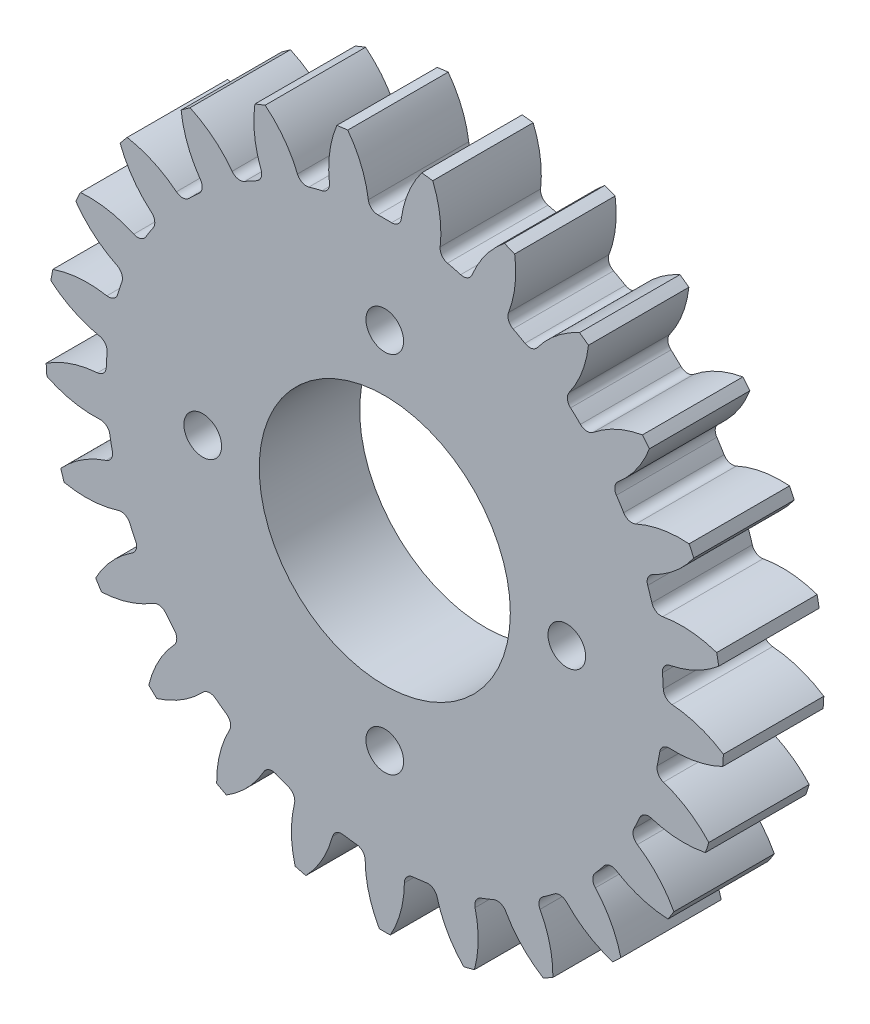
SolidWorks part; units mm, degrees
ref_plane "Front Plane" through (0, 0, 0) normal (0, 0, 1) x (1, 0, 0)
ref_plane "Top Plane" through (0, 0, 0) normal (0, 1, 0) x (1, 0, 0)
ref_plane "Right Plane" through (0, 0, 0) normal (1, 0, 0) x (0, 0, -1)
sketch "Sketch1" plane through (0, 0, 0) normal (0, 0, 1) x (1, 0, 0)
  line L0 (0, 0) -> (-18.1989, 0) construction
  line L1 (0, 0) -> (0, 8.2854) construction
  circle A0 centre (0, 0) radius 5
  circle A1 centre (0, 0) radius 13.5
  circle A2 centre (-7.25, 0) radius 0.75
  circle A3 centre (0, 7.25) radius 0.75
  circle A4 centre (7.25, 0) radius 0.75
  circle A5 centre (0, -7.25) radius 0.75
  point P19 (0, 0)
  dimension "D1" = 10
  dimension "D2" = 27
  dimension "D3" = 1.5
  dimension "D4" = 7.25
  dimension "D5" = 4
extrude "Boss-Extrude1" add sketch "Sketch1" along normal blind 10
sketch "Sketch2" plane through (0, 0, 10) normal (0, 0, 1) x (1, 0, 0)
  line L0 (0, 0) -> (0, 13.5) construction
  line L1 (-0.6232, 11.0825) -> (0, 0) construction
  line L2 (0, 9.9064) -> (-3.5205, 19.5789) construction
  circle A0 centre (0, 0) radius 13.5 construction
  arc A1 (0.6232, 11.0825) -> (-0.6232, 11.0825) centre (0, 0) ccw
  arc A2 (0.9345, 12.465) -> (-0.9345, 12.465) centre (0, 0) ccw construction
  arc A3 (-1.4738, 13.4193) -> (-0.6232, 11.0825) centre (-4.9231, 10.8407) cw
  arc A4 (1.4738, 13.4193) -> (0.6232, 11.0825) centre (4.9231, 10.8407) ccw
  point P16 (-0.8762, 12.3136)
  dimension "D1" = 25
  dimension "D2" = 2.4
  dimension "D3" = 20
  dimension "D4" = 1.8708
extrude "Cut-Extrude3" cut sketch "Sketch2" against normal blind 10 and the other way through all flip side to cut
fillet "Fillet1" radius 0.38 2 edges at (0.6232, 11.0825, 5) (-0.6232, 11.0825, 5)
pattern_circular "CirPattern1" count 25 over 360 about axis through (0, 0, 0) along (0, 0, 1) of "Cut-Extrude3", "Fillet1"
sketch "Sketch5" plane through (0, 0, 10) normal (0, 0, 1) x (1, 0, 0)
  line L0 (0, 5) -> (0, 20) construction
  circle A0 centre (0, 0) radius 5 construction
  circle A1 centre (0, 20) radius 1.5
  dimension "D2" = 3
  dimension "D1" = 15
sketch "Sketch6" plane through (0, 0, 0) normal (0, 0, 1) x (1, 0, 0)
  line L0 (0, 0) -> (-20.4531, 0) construction
  circle A0 centre (0, 0) radius 12.5
  dimension "D1" = 25
sketch "Sketch9" plane through (0, 0, 0) normal (0, 0, 1) x (1, 0, 0)
  circle A0 centre (0, 0) radius 16.2134
extrude "Cut-Extrude9" cut sketch "Sketch9" against normal through all and the other way blind 6
equation "\"No. of teeth\"= 25"
equation "\"Module\"= 1mm"
equation "\"Bore Diameter\"= 10mm"
equation "\"Pressure Angle\"= 20"
equation "\"Outer Diameter\"= ( \"No. of teeth\" + 2 ) * \"Module\""
equation "\"Pitch Diameter\"= \"No. of teeth\" * \"Module\""
equation "\"Backlash\"= 0.3 * \"Module\""
equation "\"Are Length\"= ( ( \"Module\" * pi ) / 2 ) + \"Backlash\""
equation "\"Fillet Radius\"= 0.38 * \"Module\""
equation "\"Tooth Depth\"= IIF ( \"Module\" <= 1.25 , \"Module\" * 2.4 , \"Module\" * 2.25 )"
equation "\"D1@Sketch1\"=\"Bore Diameter\""
equation "\"D2@Sketch1\"=\"Outer Diameter\""
equation "\"D1@Sketch2\"=\"Pitch Diameter\""
equation "\"D2@Sketch2\"=\"Tooth Depth\""
equation "\"D3@Sketch2\"=\"Pressure Angle\""
equation "\"D4@Sketch2\"=\"Are Length\""
equation "\"D1@Fillet1\"=\"Fillet Radius\""
equation "\"D1@CirPattern1\"=\"No. of teeth\""
equation "\"D1@Sketch6\"=\"Pitch Diameter\""
equation "\"D4@Sketch1\"=14.5/2"
